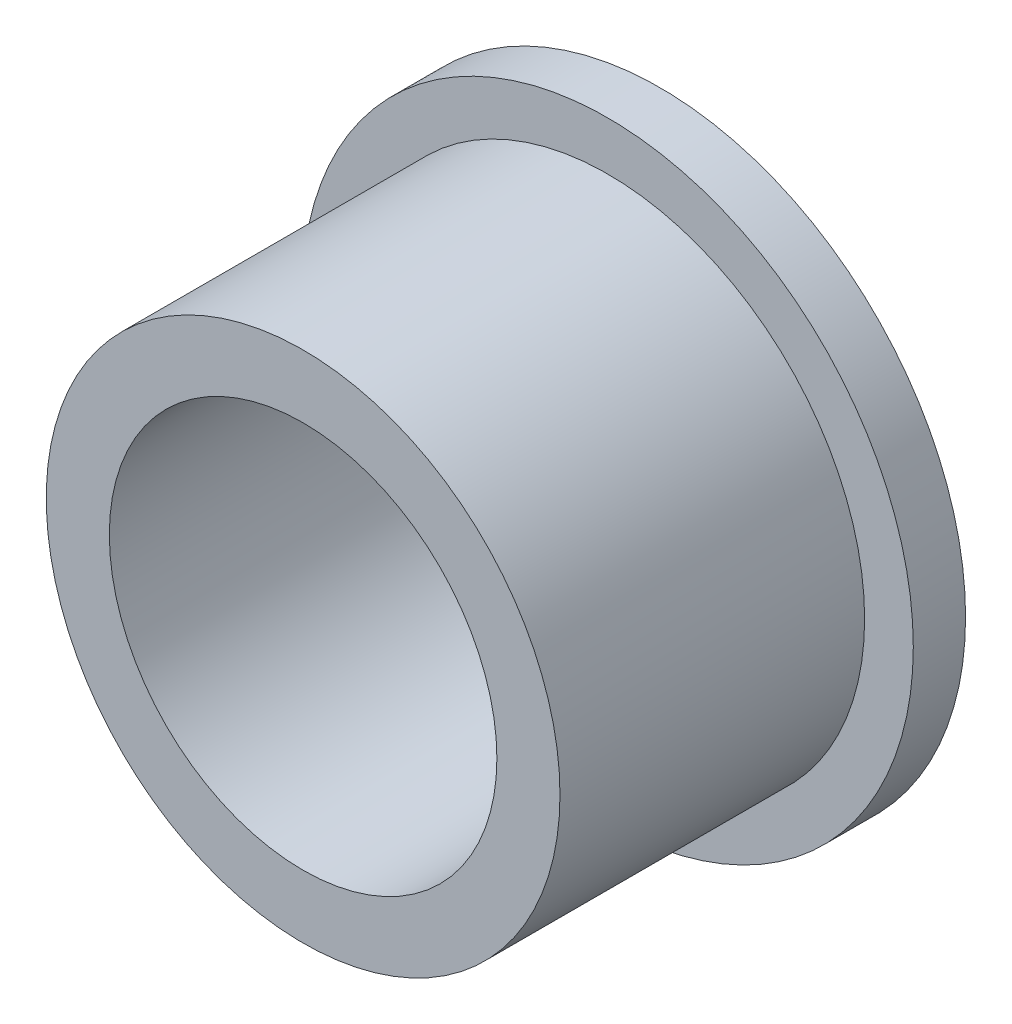
SolidWorks part; units mm, degrees
ref_plane "Front Plane" through (0, 0, 0) normal (0, 0, 1) x (1, 0, 0)
ref_plane "Top Plane" through (0, 0, 0) normal (0, 1, 0) x (1, 0, 0)
ref_plane "Right Plane" through (0, 0, 0) normal (1, 0, 0) x (0, 0, -1)
sketch "Sketch1" plane through (0, 0, 0) normal (0, 0, 1) x (1, 0, 0)
  circle A0 centre (0, 0) radius 10.75
  circle A1 centre (0, 0) radius 14.25
  circle A2 centre (0, 0) radius 16.95
  dimension "D1" = 28.5
  dimension "D2" = 33.9
  dimension "D3" = 21.5
extrude "Boss-Extrude1" add sketch "Sketch1" along normal blind 2.9 contours A2 A1 | A1 A0
sketch "Sketch2" plane through (0, 0, 2.9) normal (0, 0, 1) x (1, 0, 0)
  circle A1 centre (0, 0) radius 16.95
  circle A2 centre (0, 0) radius 16.95
  circle A3 centre (0, 0) radius 14.25
  circle A4 centre (0, 0) radius 14.25
  circle A5 centre (0, 0) radius 10.75
  circle A6 centre (0, 0) radius 10.75
  circle M5 centre (0, 0) radius 10.75
  dimension "D1" = 0
  dimension "D2" = 0
  dimension "D3" = 0
extrude "Boss-Extrude2" add sketch "Sketch2" along normal blind 16.9 contours A4 M5
